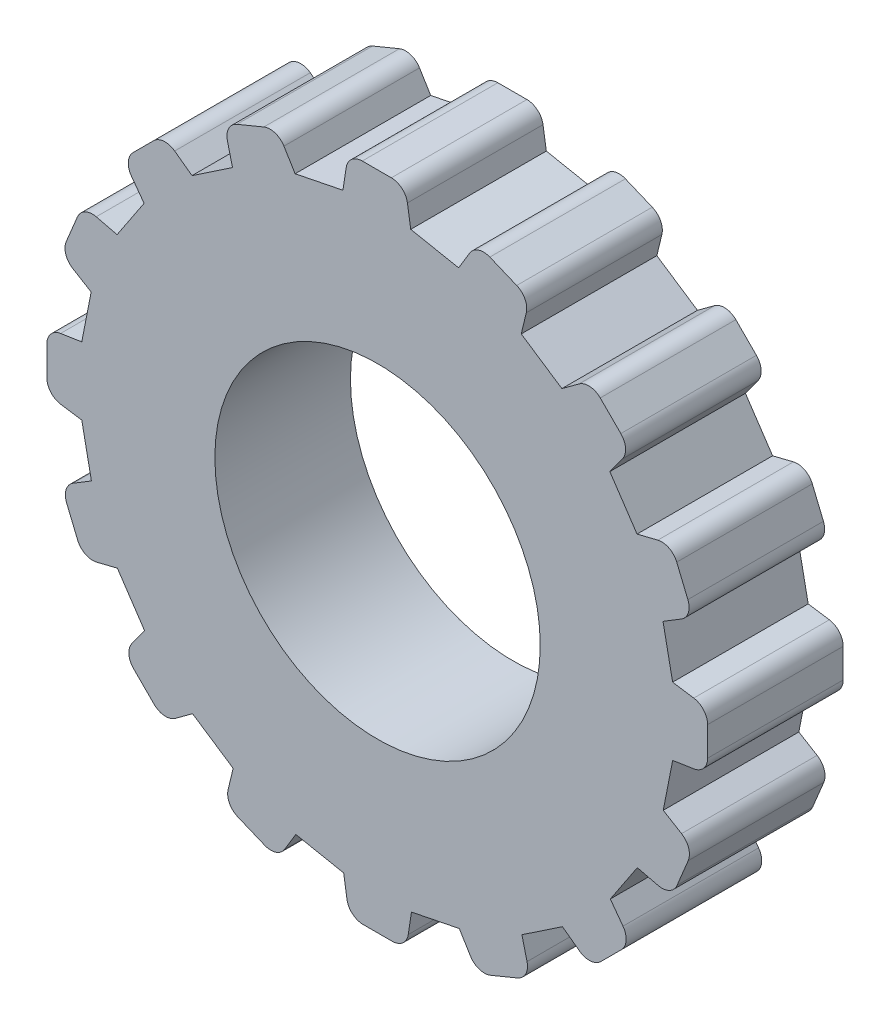
SolidWorks part; units mm, degrees
material "ABS"
ref_plane "Plan de face" through (0, 0, 0) normal (0, 0, 1) x (1, 0, 0)
ref_plane "Plan de dessus" through (0, 0, 0) normal (0, 1, 0) x (1, 0, 0)
ref_plane "Plan de droite" through (0, 0, 0) normal (1, 0, 0) x (0, 0, -1)
sketch "Esquisse5" plane through (0, 0, 0) normal (0, 0, 1) x (1, 0, 0)
  line L0 (0, 0) -> (0, 12.73) construction
  line L1 (0, 0) -> (4.8716, 11.761) construction
  line L2 (0, 12.1872) -> (0.5089, 12.1872)
  line L3 (1.1017, 11.6799) -> (1.2239, 10.8985)
  line L4 (1.2239, 10.8985) -> (2.9901, 10.5515)
  line L5 (2.9901, 10.5515) -> (3.3975, 11.2265)
  line L6 (4.1408, 11.4708) -> (4.6619, 11.2549)
  line L7 (0, 0) -> (2.107, 10.725) construction
  line L8 (4.6619, 11.2549) -> (5.1321, 11.0601)
  line L9 (5.4856, 10.3646) -> (5.2995, 9.5959)
  line L10 (5.2995, 9.5959) -> (6.7985, 8.5995)
  line L11 (6.7985, 8.5995) -> (7.4332, 9.0671)
  line L12 (8.2134, 9.0084) -> (8.6122, 8.6095)
  line L13 (8.6122, 8.6095) -> (8.9721, 8.2497)
  line L14 (9.0325, 7.4718) -> (8.5664, 6.8329)
  line L15 (8.5664, 6.8329) -> (9.57, 5.3386)
  line L16 (9.57, 5.3386) -> (10.3353, 5.5278)
  line L17 (11.0336, 5.1749) -> (11.2495, 4.6538)
  line L18 (11.2495, 4.6538) -> (11.4442, 4.1836)
  line L19 (11.2024, 3.4418) -> (10.5272, 3.03)
  line L20 (10.5272, 3.03) -> (10.8826, 1.2654)
  line L21 (10.8826, 1.2654) -> (11.6621, 1.1473)
  line L22 (12.1722, 0.554) -> (12.1722, -0.01)
  line L23 (12.1722, -0.01) -> (12.1722, -0.5189)
  line L24 (11.6649, -1.1117) -> (10.8835, -1.2339)
  line L25 (10.8835, -1.2339) -> (10.5365, -3.0001)
  line L26 (10.5365, -3.0001) -> (11.2115, -3.4075)
  line L27 (11.4558, -4.1508) -> (11.2399, -4.6719)
  line L28 (11.2399, -4.6719) -> (11.0452, -5.1421)
  line L29 (10.3496, -5.4957) -> (9.581, -5.3095)
  line L30 (9.581, -5.3095) -> (8.5845, -6.8085)
  line L31 (8.5845, -6.8085) -> (9.0522, -7.4432)
  line L32 (8.9934, -8.2234) -> (8.5946, -8.6222)
  line L33 (8.5946, -8.6222) -> (8.2347, -8.9821)
  line L34 (7.4568, -9.0425) -> (6.8179, -8.5764)
  line L35 (6.8179, -8.5764) -> (5.3236, -9.58)
  line L36 (5.3236, -9.58) -> (5.5128, -10.3453)
  line L37 (5.16, -11.0436) -> (4.6389, -11.2595)
  line L38 (4.6389, -11.2595) -> (4.1687, -11.4542)
  line L39 (3.4269, -11.2124) -> (3.015, -10.5372)
  line L40 (3.015, -10.5372) -> (1.2504, -10.8926)
  line L41 (1.2504, -10.8926) -> (1.1323, -11.6721)
  line L42 (0.5391, -12.1822) -> (-0.025, -12.1822)
  line L43 (-0.025, -12.1822) -> (-0.5339, -12.1822)
  line L44 (-1.1267, -11.6749) -> (-1.2489, -10.8935)
  line L45 (-1.2489, -10.8935) -> (-3.0151, -10.5465)
  line L46 (-3.0151, -10.5465) -> (-3.4225, -11.2215)
  line L47 (-4.1658, -11.4658) -> (-4.6869, -11.2499)
  line L48 (-4.6869, -11.2499) -> (-5.1571, -11.0552)
  line L49 (-5.5106, -10.3596) -> (-5.3245, -9.591)
  line L50 (-5.3245, -9.591) -> (-6.8235, -8.5945)
  line L51 (-6.8235, -8.5945) -> (-7.4582, -9.0622)
  line L52 (-8.2384, -9.0034) -> (-8.6372, -8.6046)
  line L53 (-8.6372, -8.6046) -> (-8.9971, -8.2447)
  line L54 (-9.0575, -7.4668) -> (-8.5914, -6.8279)
  line L55 (-8.5914, -6.8279) -> (-9.5949, -5.3336)
  line L56 (-9.5949, -5.3336) -> (-10.3603, -5.5228)
  line L57 (-11.0586, -5.17) -> (-11.2745, -4.6489)
  line L58 (-11.2745, -4.6489) -> (-11.4692, -4.1787)
  line L59 (-11.2274, -3.4369) -> (-10.5522, -3.025)
  line L60 (-10.5522, -3.025) -> (-10.9076, -1.2604)
  line L61 (-10.9076, -1.2604) -> (-11.6871, -1.1423)
  line L62 (-12.1972, -0.5491) -> (-12.1972, 0.015)
  line L63 (-12.1972, 0.015) -> (-12.1972, 0.5239)
  line L64 (-11.6899, 1.1167) -> (-10.9085, 1.2389)
  line L65 (-10.9085, 1.2389) -> (-10.5615, 3.0051)
  line L66 (-10.5615, 3.0051) -> (-11.2365, 3.4125)
  line L67 (-11.4808, 4.1558) -> (-11.2649, 4.6769)
  line L68 (-11.2649, 4.6769) -> (-11.0702, 5.1471)
  line L69 (-10.3746, 5.5006) -> (-9.6059, 5.3145)
  line L70 (-9.6059, 5.3145) -> (-8.6095, 6.8135)
  line L71 (-8.6095, 6.8135) -> (-9.0772, 7.4482)
  line L72 (-9.0184, 8.2284) -> (-8.6195, 8.6272)
  line L73 (-8.6195, 8.6272) -> (-8.2597, 8.9871)
  line L74 (-7.4818, 9.0475) -> (-6.8429, 8.5814)
  line L75 (-6.8429, 8.5814) -> (-5.3486, 9.5849)
  line L76 (-5.3486, 9.5849) -> (-5.5378, 10.3503)
  line L77 (-5.185, 11.0486) -> (-4.6638, 11.2645)
  line L78 (-4.6638, 11.2645) -> (-4.1937, 11.4592)
  line L79 (-3.4518, 11.2174) -> (-3.04, 10.5422)
  line L80 (-3.04, 10.5422) -> (-1.2754, 10.8975)
  line L81 (-1.2754, 10.8975) -> (-1.1573, 11.6771)
  line L82 (-0.5641, 12.1872) -> (0, 12.1872)
  circle A0 centre (0, 0) radius 12.73 construction
  circle A1 centre (0, 0) radius 12.23 construction
  circle A2 centre (0, 0) radius 10.93 construction
  arc A3 (4.1408, 11.4708) -> (3.3975, 11.2265) centre (3.9112, 10.9164) ccw
  arc A4 (1.1017, 11.6799) -> (0.5089, 12.1872) centre (0.5089, 11.5872) ccw
  arc A5 (8.2134, 9.0084) -> (7.4332, 9.0671) centre (7.7891, 8.5841) ccw
  arc A6 (5.4856, 10.3646) -> (5.1321, 11.0601) centre (4.9025, 10.5058) ccw
  arc A7 (11.0336, 5.1749) -> (10.3353, 5.5278) centre (10.4793, 4.9453) ccw
  arc A8 (9.0325, 7.4718) -> (8.9721, 8.2497) centre (8.5478, 7.8254) ccw
  arc A9 (12.1722, 0.554) -> (11.6621, 1.1473) centre (11.5722, 0.554) ccw
  arc A10 (11.2024, 3.4418) -> (11.4442, 4.1836) centre (10.8899, 3.954) ccw
  arc A11 (11.4558, -4.1508) -> (11.2115, -3.4075) centre (10.9015, -3.9212) ccw
  arc A12 (11.6649, -1.1117) -> (12.1722, -0.5189) centre (11.5722, -0.5189) ccw
  arc A13 (8.9934, -8.2234) -> (9.0522, -7.4432) centre (8.5691, -7.7991) ccw
  arc A14 (10.3496, -5.4957) -> (11.0452, -5.1421) centre (10.4908, -4.9125) ccw
  arc A15 (5.16, -11.0436) -> (5.5128, -10.3453) centre (4.9304, -10.4893) ccw
  arc A16 (7.4568, -9.0425) -> (8.2347, -8.9821) centre (7.8104, -8.5578) ccw
  arc A17 (0.5391, -12.1822) -> (1.1323, -11.6721) centre (0.5391, -11.5822) ccw
  arc A18 (3.4269, -11.2124) -> (4.1687, -11.4542) centre (3.9391, -10.8999) ccw
  arc A19 (-4.1658, -11.4658) -> (-3.4225, -11.2215) centre (-3.9362, -10.9115) ccw
  arc A20 (-1.1267, -11.6749) -> (-0.5339, -12.1822) centre (-0.5339, -11.5822) ccw
  arc A21 (-8.2384, -9.0034) -> (-7.4582, -9.0622) centre (-7.8141, -8.5792) ccw
  arc A22 (-5.5106, -10.3596) -> (-5.1571, -11.0552) centre (-4.9275, -10.5009) ccw
  arc A23 (-11.0586, -5.17) -> (-10.3603, -5.5228) centre (-10.5043, -4.9404) ccw
  arc A24 (-9.0575, -7.4668) -> (-8.9971, -8.2447) centre (-8.5728, -7.8204) ccw
  arc A25 (-12.1972, -0.5491) -> (-11.6871, -1.1423) centre (-11.5972, -0.5491) ccw
  arc A26 (-11.2274, -3.4369) -> (-11.4692, -4.1787) centre (-10.9149, -3.9491) ccw
  arc A27 (-11.4808, 4.1558) -> (-11.2365, 3.4125) centre (-10.9264, 3.9262) ccw
  arc A28 (-11.6899, 1.1167) -> (-12.1972, 0.5239) centre (-11.5972, 0.5239) ccw
  arc A29 (-9.0184, 8.2284) -> (-9.0772, 7.4482) centre (-8.5941, 7.8041) ccw
  arc A30 (-10.3746, 5.5006) -> (-11.0702, 5.1471) centre (-10.5158, 4.9175) ccw
  arc A31 (-5.185, 11.0486) -> (-5.5378, 10.3503) centre (-4.9553, 10.4943) ccw
  arc A32 (-7.4818, 9.0475) -> (-8.2597, 8.9871) centre (-7.8354, 8.5628) ccw
  arc A33 (-0.5641, 12.1872) -> (-1.1573, 11.6771) centre (-0.5641, 11.5872) ccw
  arc A34 (-3.4518, 11.2174) -> (-4.1937, 11.4592) centre (-3.964, 10.9049) ccw
  circle A36 centre (0, 0) radius 6
  point P15 (3.6641, 11.6682)
  point P19 (1.0224, 12.1872)
  point P172 (-0.0125, 0.0025)
  dimension "D1" = 25.46
  dimension "D8" = 0.6
  dimension "D10" = 12
  dimension "D2" = 22.5
  dimension "D3" = 0.5
  dimension "D4" = 1.3
  dimension "D5" = 20
  dimension "D6" = 20
  dimension "D7" = 1.8
  dimension "D9" = 16
extrude "Boss.-Extru.1" add sketch "Esquisse5" along normal blind 5
equation "\"A\"= 26"
equation "\"E\"= 20.5"
equation "\"C\"= 6"
equation "\"B\"= 16.5"
equation "\"Dp\"= 25.46'Diamètre primitif"
equation "\"Df\"= 28'Diamètre extérieur"
equation "\"Teeth\"= 16'Nombre de dents"
equation "\"L\"= 15'Largeur courroie"
equation "\"D1\" = \"A\" - \"E\" - 2"
equation "\"D1@Esquisse3\"=\"L\"+2"
equation "\"D2@Esquisse3\"=\"Dp\"/2-5"
equation "\"D1@Esquisse5\"=\"Dp\""
equation "\"D2@Esquisse5\"=360/\"Teeth\""
